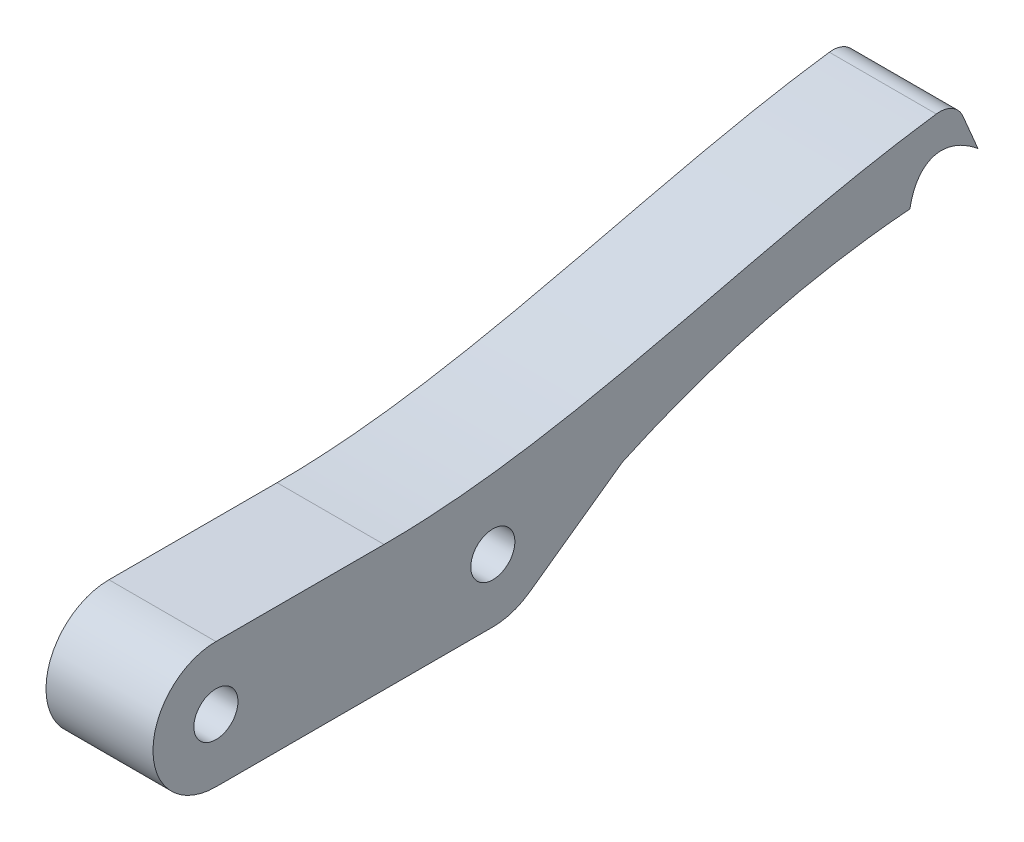
SolidWorks part; units mm, degrees
ref_plane "Front Plane" through (0, 0, 0) normal (0, 0, 1) x (1, 0, 0)
ref_plane "Top Plane" through (0, 0, 0) normal (0, 1, 0) x (1, 0, 0)
ref_plane "Right Plane" through (0, 0, 0) normal (1, 0, 0) x (0, 0, -1)
sketch "Sketch1" plane through (0, 0, 0) normal (1, 0, 0) x (0, 0, -1)
  line L1 (0, 0) -> (27, 0)
  line L2 (0, 0) -> (0, 10)
  line L3 (0, 10) -> (27, 10)
  circle A0 centre (5, 5) radius 1.75
  circle A1 centre (5, 5) radius 5
  circle A2 centre (27, 5) radius 5
  circle A3 centre (27, 5) radius 1.75
  dimension "D7" = 3.5
  dimension "D11" = 10
  dimension "D2" = 3.5
  dimension "D1" = 10
  dimension "D8" = 5
  dimension "D9" = 5
  dimension "D10" = 22
extrude "Boss-Extrude1" add sketch "Sketch1" along normal blind 8.5 contours A1 A0 | A2 L3 A1 L1 | A2 A3 | L2 A1 | L1 A1
sketch "Sketch2" plane through (8.5, 0, 0) normal (1, 0, 0) x (0, 0, -1)
  line L6 (5, 10) -> (27, 10) construction
  line L14 (5, 10) -> (27, 10)
  line L20 (29.9035, 0.9294) -> (37.2779, 6.1894)
  line L21 (60.7102, 12.2385) -> (65.5891, 13.54)
  line L22 (65.5891, 13.54) -> (63.753, 17.8724)
  arc A3 (27, 0) -> (27, 10) centre (27, 5) ccw construction
  arc A4 (27, 0) -> (27, 10) centre (27, 5) ccw
  spline S0 degree 2 poles (37.2779, 6.1894) (48.4256, 11.3441) (60.7102, 12.2385) knots 0 0 0 1 1 1
  spline S1 degree 3 poles (63.753, 17.8724) (48.4484, 16.0759) (33.9276, 10) (18.3574, 10) knots 0 0 0 0 1 1 1 1
  point P2 (27, 5)
  dimension "D1" = 67.033
extrude "Boss-Extrude2" add sketch "Sketch2" against normal blind 8.5
ref_plane "Plane1" through (4.25, 0, 0) normal (-1, 0, 0) x (0, 0, 1)
sketch "Sketch3" plane through (4.25, 0, 0) normal (-1, 0, 0) x (0, 0, 1)
  line L0 (-63.753, 17.8724) -> (-73.284, -4.6168) construction
  line L1 (-61.4795, 15.5486) -> (-70.4543, -5.6281) construction
  line L2 (-60.7102, 12.2385) -> (-65.5891, 13.54) construction
  line L3 (-61.3633, 3.0092) -> (-70.5705, 6.9113)
  ellipse E0 centre (-65.9669, 4.9603) end of major axis (-70.4543, -5.6281) minor radius 5 (-61.3633, 3.0092) -> (-70.5705, 6.9113) ccw
  point P11 (0, 0)
  point P14 (-65.9669, 4.9603)
  dimension "D1" = 2
  dimension "D2" = 10
  dimension "D3" = 23
  dimension "D4" = 3
revolve "Cut-Revolve1" cut sketch "Sketch3" angle 360 about L3
fillet "Fillet1" radius 2 1 edges at (4.25, 17.8724, -63.753)
ref_plane "Plane4" through (0, 24.4556, -57.7047) normal (0, 0.3902, -0.9207) x (0, -0.9207, -0.3902)
ref_plane "Plane3" through (0, 24.4556, -57.7047) normal (0, 0.3902, -0.9207) x (0, -0.9207, -0.3902)
sketch "Sketch4" plane through (0, 24.4556, -57.7047) normal (0, 0.3902, -0.9207) x (0, -0.9207, -0.3902)
  line L0 (21.1738, 0.75) -> (21.1738, -9.25)
  ellipse E0 centre (21.1738, -4.25) end of major axis (9.6738, -4.25) minor radius 5 (21.1738, 0.75) -> (21.1738, -9.25) ccw
  point P2 (0, 0)
  point P10 (0, 0)
  point P11 (0, 0)
  dimension "D2" = 10
revolve "Cut-Revolve4" cut sketch "Sketch4" angle 360 about L0
